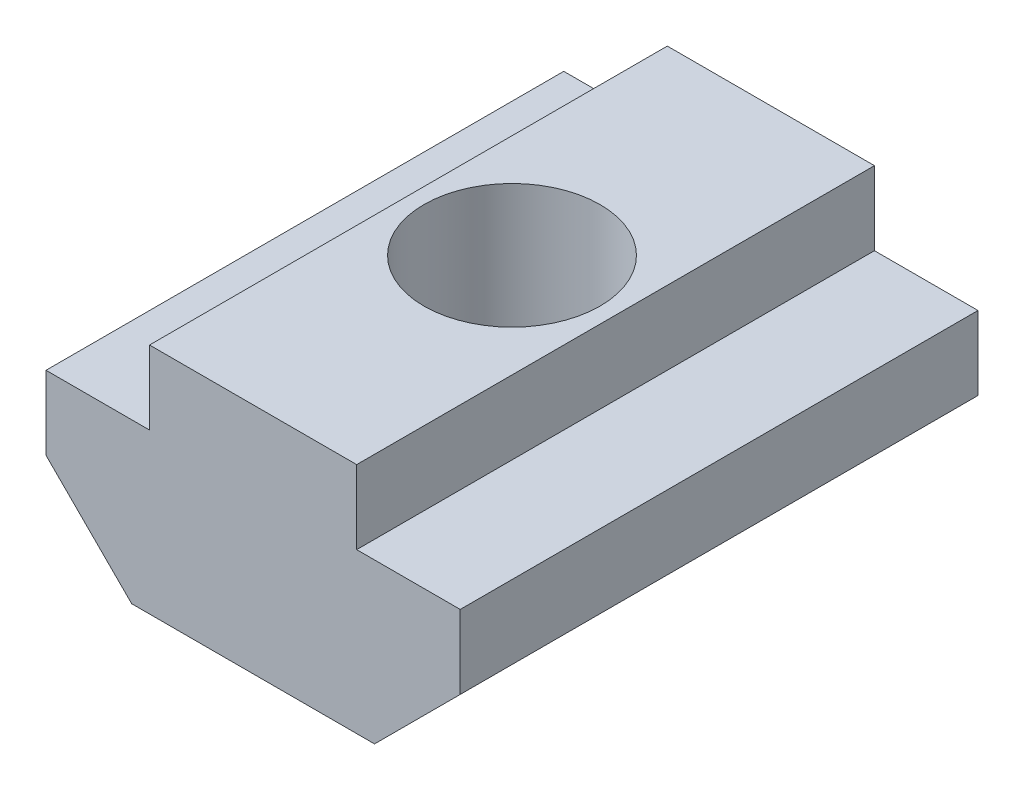
SolidWorks part; units mm, degrees
material "Plain Carbon Steel"
ref_plane "Front Plane" through (0, 0, 0) normal (0, 0, 1) x (1, 0, 0)
ref_plane "Top Plane" through (0, 0, 0) normal (0, 1, 0) x (1, 0, 0)
ref_plane "Right Plane" through (0, 0, 0) normal (1, 0, 0) x (0, 0, -1)
ref_plane "Plane1"
sketch "Sketch1" plane through (0, 0, 0) normal (0, 0, 1) x (1, 0, 0)
  line L0 (2.9635, 0.3899) -> (-0.3469, 3.7003)
  line L1 (-0.3469, 3.7003) -> (-0.3469, 6.5451)
  line L2 (-0.3469, 6.5451) -> (3.6526, 6.5451)
  line L3 (3.6526, 6.5451) -> (3.6526, 9.3899)
  line L4 (3.6526, 9.3899) -> (11.6536, 9.3899)
  line L5 (11.6536, 9.3899) -> (11.6536, 6.5451)
  line L6 (11.6536, 6.5451) -> (15.6531, 6.5451)
  line L7 (15.6531, 6.5451) -> (15.6531, 3.7003)
  line L8 (15.6531, 3.7003) -> (12.3427, 0.3899)
  line L9 (12.3427, 0.3899) -> (2.9635, 0.3899)
  dimension "D1" = 16
  dimension "D2" = 8.001
  dimension "D3" = 9
  dimension "D4" = 2.8448
  dimension "D5" = 2.8448
  dimension "D6" = 135
extrude "Extrusion1" add sketch "Sketch1" along normal blind 20
hole_wizard "Hole2" positions "Sketch3" profile "Sketch2" tap size "M8x1.25" standard "Macron Ansi Metric" end condition through all
sketch "Sketch3" plane through (0, 0.3899, 0) normal (0, -1, 0) x (1, 0, 0)
  point P1 (7.6531, 10)
sketch "Sketch2" plane through (7.6531, 0.3899, 10) normal (1, 0, 0) x (0, 0, -1)
  line L0 (0, 0) -> (0, 9)
  line L1 (0, 9) -> (3.4, 9)
  line L2 (3.4, 9) -> (3.4, 0)
  line L5 (3.4, 0) -> (0, 0)
  line L11 (0, -6.35) -> (0, 107.95) construction
  dimension "Thru Tap Drill Dia." = 6.8
  dimension "Thru Tap Drill Depth" = 9
cosmetic thread "Hole Thread1" parameters "D2"=8
